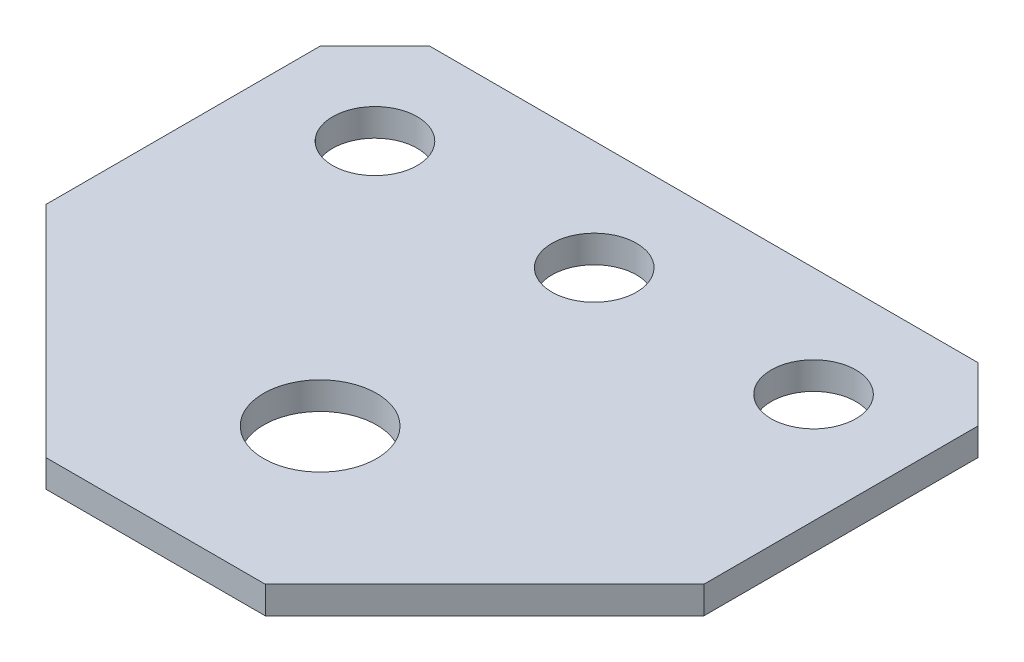
SolidWorks part; units mm, degrees
ref_plane "Front Plane" through (0, 0, 0) normal (0, 0, 1) x (1, 0, 0)
ref_plane "Top Plane" through (0, 0, 0) normal (0, 1, 0) x (1, 0, 0)
ref_plane "Right Plane" through (0, 0, 0) normal (1, 0, 0) x (0, 0, -1)
sketch "Sketch1" plane through (0, 0, 0) normal (0, 1, 0) x (1, 0, 0)
  line L1 (-38.1, 31.75) -> (38.1, 31.75)
  line L2 (-38.1, 31.75) -> (-38.1, -31.75)
  line L3 (-38.1, -31.75) -> (38.1, -31.75)
  line L4 (38.1, 31.75) -> (38.1, -31.75)
  line L5 (-38.1, 31.75) -> (38.1, -31.75) construction
  line L6 (-38.1, -31.75) -> (38.1, 31.75) construction
  point P0 (0, 0)
  dimension "D1" = 76.2
  dimension "D2" = 63.5
extrude "Boss-Extrude1" add sketch "Sketch1" along normal mid plane 3.175
hole_wizard "3/8 Clearance Hole1" positions "Sketch2" profile "Sketch3" hole size "3/8" standard "ANSI Inch" end condition through all
sketch "Sketch2" plane through (0, 1.5875, 0) normal (0, 1, 0) x (1, 0, 0)
  line L0 (0, 31.75) -> (0, -31.75) construction
  line L1 (38.1, 31.75) -> (-38.1, 31.75) construction
  line L2 (-38.1, -31.75) -> (38.1, -31.75) construction
  line L4 (-38.1, 31.75) -> (-38.1, 19.05) construction
  line L5 (-38.1, 31.75) -> (-38.1, -31.75) construction
  line L7 (-38.1, 19.05) -> (38.1, 19.05) construction
  line L8 (38.1, -31.75) -> (38.1, 31.75) construction
  circle A0 centre (0, -10.9678) radius 6.3662
  point P0 (0, 19.05)
  point P3 (25.4, 19.05)
  point P34 (-25.4, 19.05)
  dimension "D3" = 10.9678
  dimension "D1" = 12.7
  dimension "D2" = 25.4
sketch "Sketch3" plane through (0, 1.5875, -19.05) normal (1, 0, 0) x (0, 0, 1)
  line L0 (0, 0) -> (0, 3.175)
  line L1 (0, 3.175) -> (4.9022, 3.175)
  line L2 (4.9022, 3.175) -> (4.9022, 0)
  line L5 (4.9022, 0) -> (0, 0)
  line L11 (0, -6.35) -> (0, 107.95) construction
  dimension "Thru Hole Dia." = 9.8044
  dimension "Thru Hole Depth" = 3.175
hole_wizard "1/2 Clearance Hole1" positions "Sketch5" profile "Sketch6" hole size "1/2" standard "ANSI Inch" end condition through all
sketch "Sketch5" plane through (0, 1.5875, 0) normal (0, 1, 0) x (1, 0, 0)
  line L0 (-38.1, -31.75) -> (38.1, -31.75) construction
  point P0 (0, -12.7)
  dimension "D1" = 19.05
sketch "Sketch6" plane through (0, 1.5875, 12.7) normal (1, 0, 0) x (0, 0, 1)
  line L0 (0, 0) -> (0, 3.175)
  line L1 (0, 3.175) -> (6.5481, 3.175)
  line L2 (6.5481, 3.175) -> (6.5481, 0)
  line L5 (6.5481, 0) -> (0, 0)
  line L11 (0, -6.35) -> (0, 107.95) construction
  dimension "Thru Hole Dia." = 13.0962
  dimension "Thru Hole Depth" = 3.175
chamfer "Chamfer1" distance 25.4 angle 45 2 edges at (-38.1, 0, 31.75) (38.1, 0, 31.75)
chamfer "Chamfer2" distance 6.35 angle 45 2 edges at (-38.1, 0, -31.75) (38.1, 0, -31.75)
